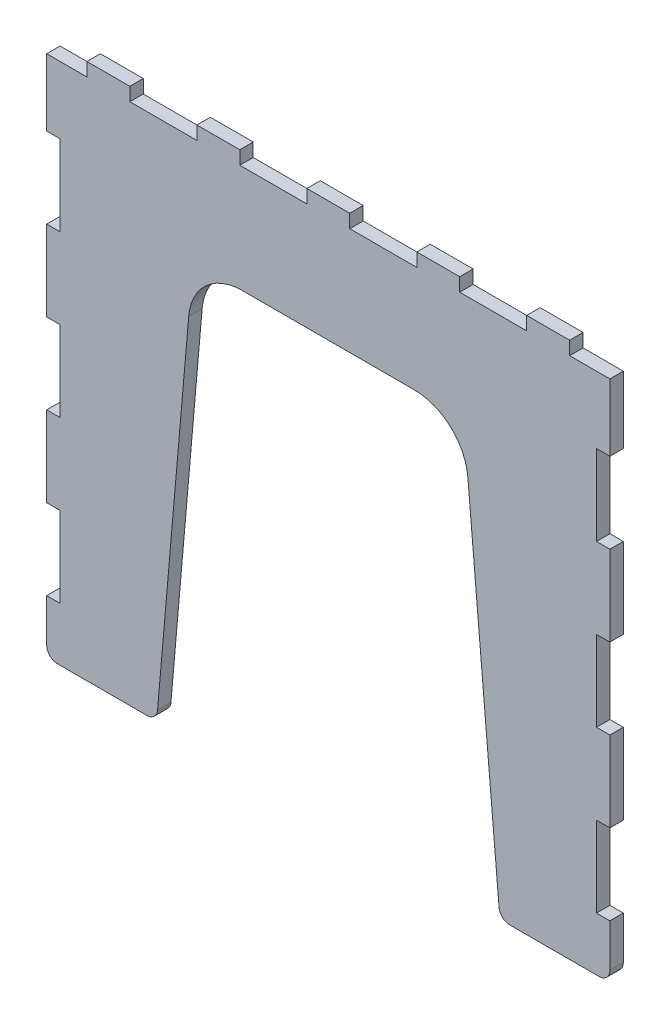
SolidWorks part; units mm, degrees
material "Beech"
ref_plane "Front" through (0, 0, 0) normal (0, 0, 1) x (1, 0, 0)
ref_plane "Top" through (0, 0, 0) normal (0, 1, 0) x (1, 0, 0)
ref_plane "Right" through (0, 0, 0) normal (1, 0, 0) x (0, 0, -1)
sketch "Sketch1" plane through (0, 0, 0) normal (0, 0, 1) x (1, 0, 0)
  line L0 (-50, 0) -> (50, 0) construction
  line L1 (-50, 0) -> (-50, -97.5) construction
  line L2 (50, 0) -> (50, -97.5) construction
  line L3 (-25.2196, -20) -> (-32, -97.5)
  line L4 (-25.2196, -20) -> (25.2196, -20)
  line L5 (25.2196, -20) -> (32, -97.5)
  line L6 (-52.5, 2.5) -> (-52.5, -97.5) construction
  line L7 (-52.5, 2.5) -> (52.5, 2.5) construction
  line L8 (52.5, 2.5) -> (52.5, -97.5) construction
  line L9 (50, 0) -> (52.5, 0)
  line L10 (52.5, 0) -> (52.5, -12.5)
  line L11 (52.5, -12.5) -> (50, -12.5)
  line L12 (50, -12.5) -> (50, -27.5)
  line L13 (52.5, -27.5) -> (52.5, -42.5)
  line L14 (52.5, -42.5) -> (50, -42.5)
  line L15 (50, -42.5) -> (50, -57.5)
  line L16 (50, -27.5) -> (52.5, -27.5)
  line L17 (52.5, -57.5) -> (52.5, -72.5)
  line L18 (52.5, -72.5) -> (50, -72.5)
  line L19 (50, -72.5) -> (50, -87.5)
  line L20 (50, -57.5) -> (52.5, -57.5)
  line L21 (50, -87.5) -> (52.5, -87.5)
  line L22 (52.5, -87.5) -> (52.5, -97.5)
  line L23 (52.5, -97.5) -> (32, -97.5)
  line L24 (50, 0) -> (45, 0)
  line L25 (45, 0) -> (45, 2.5)
  line L26 (45, 2.5) -> (37, 2.5)
  line L27 (37, 2.5) -> (37, 0)
  line L28 (37, 0) -> (24.5, 0)
  line L29 (24.5, 0) -> (24.5, 2.5)
  line L30 (24.5, 2.5) -> (16.5, 2.5)
  line L31 (16.5, 2.5) -> (16.5, 0)
  line L32 (16.5, 0) -> (4, 0)
  line L33 (4, 0) -> (4, 2.5)
  line L34 (4, 2.5) -> (-4, 2.5)
  line L35 (0, 20.5883) -> (0, -11.3086) construction
  line L36 (-52.5, -97.5) -> (-32, -97.5)
  line L37 (-52.5, -87.5) -> (-52.5, -97.5)
  line L38 (-50, -87.5) -> (-52.5, -87.5)
  line L39 (-50, -72.5) -> (-50, -87.5)
  line L40 (-52.5, -72.5) -> (-50, -72.5)
  line L41 (-52.5, -57.5) -> (-52.5, -72.5)
  line L42 (-50, -57.5) -> (-52.5, -57.5)
  line L43 (-50, -42.5) -> (-50, -57.5)
  line L44 (-52.5, -42.5) -> (-50, -42.5)
  line L45 (-52.5, -27.5) -> (-52.5, -42.5)
  line L46 (-50, -27.5) -> (-52.5, -27.5)
  line L47 (-50, -12.5) -> (-50, -27.5)
  line L48 (-52.5, -12.5) -> (-50, -12.5)
  line L49 (-52.5, 0) -> (-52.5, -12.5)
  line L50 (-50, 0) -> (-52.5, 0)
  line L51 (-50, 0) -> (-45, 0)
  line L52 (-45, 0) -> (-45, 2.5)
  line L53 (-45, 2.5) -> (-37, 2.5)
  line L54 (-37, 2.5) -> (-37, 0)
  line L55 (-37, 0) -> (-24.5, 0)
  line L56 (-24.5, 0) -> (-24.5, 2.5)
  line L57 (-24.5, 2.5) -> (-16.5, 2.5)
  line L58 (-16.5, 2.5) -> (-16.5, 0)
  line L59 (-16.5, 0) -> (-4, 0)
  line L60 (-4, 0) -> (-4, 2.5)
  point P4 (0, 0)
  point P6 (52.5, -27.5)
  point P37 (-22, -20)
  point P64 (0, 2.5)
  point P65 (22, -20)
  dimension "D1" = 100
  dimension "D2" = 97.5
  dimension "D5" = 15
  dimension "D7" = 8
  dimension "D8" = 5
  dimension "D9" = 12.5
  dimension "D3" = 20
  dimension "D6" = 95
  dimension "D10" = 95
  dimension "D11" = 20.5
  dimension "D12" = 12.5
  dimension "D4" = 2.5
extrude "Boss-Extrude1" add sketch "Sketch1" along normal blind 2.5
fillet "Fillet1" radius 2 4 edges at (52.5, -97.5, 1.25) (32, -97.5, 1.25) (-32, -97.5, 1.25) (-52.5, -97.5, 1.25)
fillet "Fillet2" radius 10 2 edges at (-25.2196, -20, 1.25) (25.2196, -20, 1.25)
